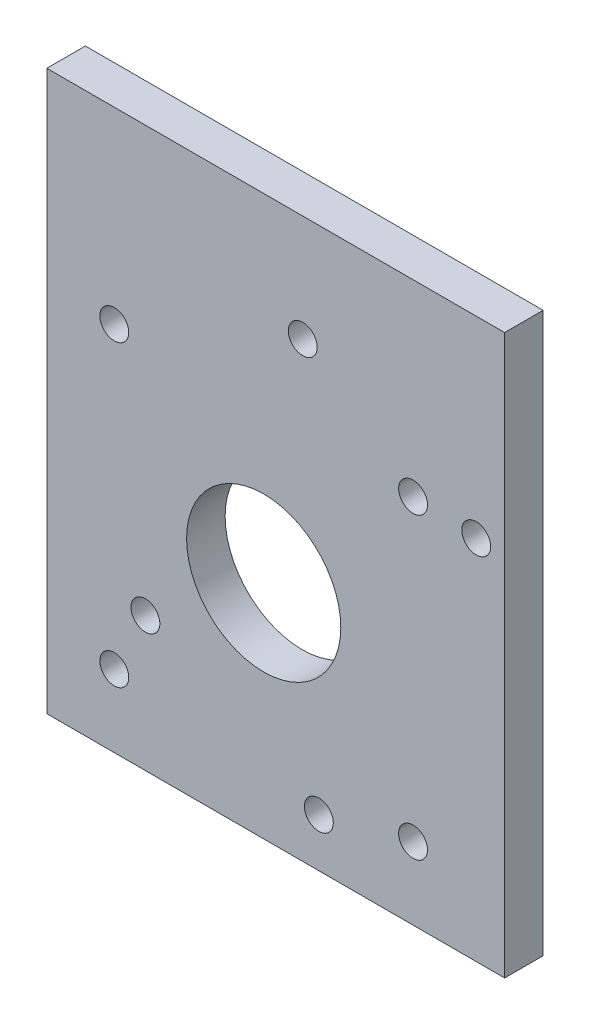
SolidWorks part; units mm, degrees
ref_plane "Front Plane" through (0, 0, 0) normal (0, 0, 1) x (1, 0, 0)
ref_plane "Top Plane" through (0, 0, 0) normal (0, 1, 0) x (1, 0, 0)
ref_plane "Right Plane" through (0, 0, 0) normal (1, 0, 0) x (0, 0, -1)
sketch "Sketch1" plane through (0, 0, 0) normal (0, 0, 1) x (1, 0, 0)
  line L1 (-21.25, 20) -> (21.25, 20)
  line L2 (-21.25, 20) -> (-21.25, -20)
  line L3 (-21.25, -20) -> (21.25, -20)
  line L4 (21.25, 20) -> (21.25, -20)
  line L5 (-21.25, 20) -> (21.25, -20) construction
  line L6 (-21.25, -20) -> (21.25, 20) construction
  point P0 (0, 0)
  dimension "D1" = 42.5
  dimension "D2" = 40
extrude "Boss-Extrude1" add sketch "Sketch1" along normal mid plane 4
sketch "Sketch2" plane through (0, 0, -2) normal (0, 0, -1) x (-1, 0, 0)
  line L0 (21.25, -20) -> (-21.25, -20) construction
  line L1 (-21.25, -20) -> (-21.25, 20) construction
  circle A0 centre (-16.75, 15.5) radius 1.5
  circle A1 centre (14.25, 15.5) radius 1.5
  circle A2 centre (14.25, -15.5) radius 1.5
  circle A3 centre (-16.75, -15.5) radius 1.5
  dimension "D1" = 3
  dimension "D2" = 31
  dimension "D3" = 31
  dimension "D4" = 4.5
  dimension "D5" = 4.5
extrude "Cut-Extrude1" cut sketch "Sketch2" against normal blind 4
sketch "Sketch3" plane through (0, 0, 2) normal (0, 0, 1) x (1, 0, 0)
  line L0 (21.25, -20) -> (21.25, 20) construction
  line L1 (-21.25, -20) -> (21.25, -20) construction
  circle A7 centre (1.25, 0) radius 8
  dimension "D2" = 20
  dimension "D1" = 20
  dimension "D3" = 16
extrude "Cut-Extrude2" cut sketch "Sketch3" against normal blind 4
ref_point "Point1"
sketch "Sketch4" plane through (0, 20, 0) normal (0, 1, 0) x (1, 0, 0)
  line L1 (-21.25, 2) -> (21.25, 2)
  line L2 (-21.25, 2) -> (-21.25, -2)
  line L3 (-21.25, -2) -> (21.25, -2)
  line L4 (21.25, 2) -> (21.25, -2)
extrude "Boss-Extrude2" add sketch "Sketch4" along normal blind 15
sketch "Sketch8" plane through (21.25, 0, 0) normal (1, 0, 0) x (0, 0, -1)
  line L1 (-2, 35) -> (2, 35)
  line L2 (-2, 35) -> (-2, -20)
  line L3 (-2, -20) -> (2, -20)
  line L4 (2, 35) -> (2, -20)
extrude "Boss-Extrude3" add sketch "Sketch8" along normal blind 5
sketch "Sketch7" plane through (0, 0, 2) normal (0, 0, 1) x (1, 0, 0)
  circle A0 centre (5.3038, 23.9455) radius 1.5
  circle A1 centre (23.3035, 15.0393) radius 1.5
  circle A2 centre (6.9755, -17.9601) radius 1.5
  circle A3 centre (-11.0242, -9.0539) radius 1.5
  dimension "D1" = 3
  dimension "D2" = 17.9997
  dimension "D3" = 32.9994
  dimension "D4" = 17.9997
  dimension "D5" = 32.9994
  dimension "D6" = 9.0539
extrude "Cut-Extrude3" cut sketch "Sketch7" against normal blind 10
sketch "Sketch9" plane through (0, -20, 0) normal (0, -1, 0) x (1, 0, 0)
  line L1 (-21.25, 2) -> (26.25, 2)
  line L2 (-21.25, 2) -> (-21.25, -2)
  line L3 (-21.25, -2) -> (26.25, -2)
  line L4 (26.25, 2) -> (26.25, -2)
extrude "Boss-Extrude4" add sketch "Sketch9" along normal blind 3
